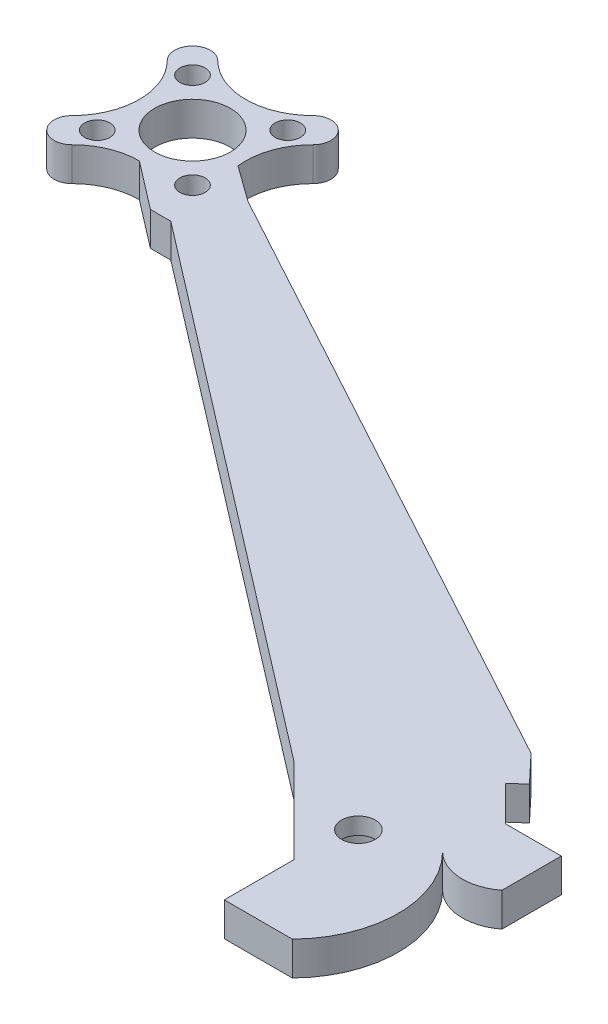
SolidWorks part; units mm, degrees
material "ABS"
ref_plane "Front Plane" through (0, 0, 0) normal (0, 0, 1) x (1, 0, 0)
ref_plane "Top Plane" through (0, 0, 0) normal (0, 1, 0) x (1, 0, 0)
ref_plane "Right Plane" through (0, 0, 0) normal (1, 0, 0) x (0, 0, -1)
sketch "Sketch1" plane through (0, 0, 0) normal (0, 1, 0) x (1, 0, 0)
  line L1 (8.155, -8.155) -> (-8.155, -8.155)
  line L2 (8.155, -8.155) -> (8.155, 8.155)
  line L3 (8.155, 8.155) -> (-8.155, 8.155)
  line L4 (-8.155, -8.155) -> (-8.155, 8.155)
  line L5 (8.155, -8.155) -> (-8.155, 8.155) construction
  line L6 (8.155, 8.155) -> (-8.155, -8.155) construction
  circle A0 centre (0, 0) radius 4.5
  dimension "D1" = 9
  dimension "D2" = 16.31
  dimension "D3" = 16.31
extrude "Boss-Extrude1" add sketch "Sketch1" along normal blind 4
sketch "Sketch3" plane through (0, 4, 0) normal (0, 1, 0) x (1, 0, 0)
  line L0 (0, 0) -> (0, 8.155) construction
  line L1 (8.155, 8.155) -> (-8.155, 8.155) construction
  line L2 (0, 0) -> (-8.155, 0) construction
  line L3 (-8.155, 8.155) -> (-8.155, -8.155) construction
  line L4 (0, 0) -> (0, -8.155) construction
  line L5 (-8.155, -8.155) -> (8.155, -8.155) construction
  line L6 (0, 0) -> (8.155, 0) construction
  line L7 (8.155, -8.155) -> (8.155, 8.155) construction
  line L8 (0, 0) -> (5.6569, 5.6569) construction
  line L9 (0, 0) -> (5.6569, -5.6569) construction
  line L10 (0, 0) -> (-5.6569, -5.6569) construction
  line L11 (0, 0) -> (-5.6569, 5.6569) construction
  circle A0 centre (5.6569, 5.6569) radius 1.5
  circle A1 centre (5.6569, -5.6569) radius 1.5
  circle A2 centre (-5.6569, -5.6569) radius 1.5
  circle A3 centre (-5.6569, 5.6569) radius 1.5
  point P22 (0, 0)
  point P29 (0, 0)
  dimension "D2" = 3
  dimension "D1" = 4
  dimension "D3" = 4
extrude "Cut-Extrude1" cut sketch "Sketch3" against normal blind 4
sketch "Sketch4" plane through (0, 4, 0) normal (0, 1, 0) x (1, 0, 0)
  line L0 (8.155, -8.155) -> (0, -8.155)
  line L1 (-8.155, -8.155) -> (8.155, -8.155) construction
  line L2 (8.155, -8.155) -> (8.155, 0)
  line L3 (8.155, -8.155) -> (8.155, 8.155) construction
  line L4 (0, -8.155) -> (0, -10.655)
  line L5 (8.155, 0) -> (10.655, 0)
  line L6 (0, -10.655) -> (10.655, -10.655)
  line L7 (10.655, -10.655) -> (10.655, 0)
extrude "Boss-Extrude2" add sketch "Sketch4" against normal blind 4
sketch "Sketch9" plane through (0, 4, 0) normal (0, 1, 0) x (1, 0, 0)
  line L0 (71.0614, -58.9826) -> (7.5931, -10.2817)
  line L1 (84.1935, -43.9826) -> (10.6138, -4.0321)
  line L2 (71.0614, -58.9826) -> (81.0614, -68.9826)
  line L3 (7.5931, -10.2817) -> (10.6138, -4.0321)
  line L4 (81.0614, -68.9826) -> (81.0614, -73.9826)
  line L5 (81.0614, -73.9826) -> (96.0614, -73.9826)
  line L6 (96.0614, -73.9826) -> (96.0614, -50.291)
  line L7 (96.0614, -50.291) -> (90.502, -50.291)
  line L8 (90.502, -50.291) -> (84.1935, -43.9826)
extrude "Boss-Extrude6" add sketch "Sketch9" against normal blind 4
sketch "Sketch12" plane through (0, 4, 0) normal (0, 1, 0) x (1, 0, 0)
  line L0 (87.2786, -47.2583) -> (85.7805, -48.5833)
  line L1 (85.7805, -48.5833) -> (89.9609, -52.761)
  line L2 (89.9609, -52.761) -> (90.502, -52.761)
  line L3 (90.502, -52.761) -> (96.0614, -52.761)
  line L4 (96.0614, -52.761) -> (96.0614, -50.291)
  line L5 (87.3477, -47.1368) -> (90.502, -50.291)
  line L6 (90.502, -50.291) -> (96.0614, -50.291)
  line L7 (90.502, -50.291) -> (96.0614, -50.291)
  line L8 (87.2786, -47.2583) -> (87.3477, -47.1368)
extrude "Cut-Extrude3" cut sketch "Sketch12" against normal blind 4 contours L8 L5 L6 L4 L3 L2 L1 L0
sketch "Sketch13" plane through (0, 4, 0) normal (0, 1, 0) x (1, 0, 0)
  line L0 (81.0614, -73.9826) -> (81.0614, -77.2826)
  line L1 (96.0614, -52.761) -> (96.5614, -52.761)
  line L2 (81.0614, -73.9826) -> (96.0614, -73.9826)
  line L3 (96.0614, -73.9826) -> (96.0614, -52.761)
  line L4 (96.5614, -52.761) -> (96.5614, -77.2826)
  line L5 (81.0614, -77.2826) -> (96.5614, -77.2826)
  dimension "D1" = 3.3
  dimension "D2" = 0.5
extrude "Boss-Extrude7" add sketch "Sketch13" against normal blind 4
sketch "Sketch16" plane through (0, 4, 0) normal (0, 1, 0) x (1, 0, 0)
  line L0 (0, -10.655) -> (-10, -10.655)
  line L1 (-10, -10.655) -> (-10, 10.345)
  line L2 (10.655, 0) -> (10.655, 10.345)
  line L3 (10.655, 10.345) -> (-10, 10.345)
  line L4 (0, -10.655) -> (0, -8.155)
  line L5 (0, -8.155) -> (-8.155, -8.155)
  line L6 (-8.155, -8.155) -> (-8.155, 8.155)
  line L7 (-8.155, 8.155) -> (8.155, 8.155)
  line L8 (8.155, 8.155) -> (8.155, 0)
  line L9 (8.155, 0) -> (10.655, 0)
  dimension "D1" = 10
  dimension "D2" = 21
extrude "Boss-Extrude9" add sketch "Sketch16" against normal blind 4
sketch "Sketch17" plane through (0, 4, 0) normal (0, 1, 0) x (1, 0, 0)
  line L0 (-5.6569, 5.6569) -> (-5.6569, 8.6569) construction
  line L1 (-5.6569, 5.6569) -> (-8.6569, 5.6569) construction
  line L2 (5.6569, 5.6569) -> (5.6569, 8.6569) construction
  line L3 (5.6569, 5.6569) -> (8.6569, 5.6569) construction
  line L4 (-5.6569, -5.6569) -> (-8.6569, -5.6569) construction
  line L5 (-5.6569, -5.6569) -> (-5.6569, -8.6569) construction
  line L6 (5.6569, -5.6569) -> (8.6569, -5.6569) construction
  line L7 (5.6569, -5.6569) -> (5.6569, -8.6569) construction
  line L8 (5.6569, -8.6569) -> (5.6569, -10.655)
  line L9 (-10, -10.655) -> (8.0797, -10.655) construction
  line L10 (8.6569, -5.6569) -> (10.655, -4.0544)
  line L11 (5.6569, -10.655) -> (8.0797, -10.655)
  line L12 (8.0797, -10.655) -> (71.0614, -58.9826)
  line L13 (71.0614, -58.9826) -> (81.0614, -68.9826)
  line L14 (81.0614, -68.9826) -> (81.0614, -77.2826)
  line L15 (81.0614, -77.2826) -> (96.5614, -77.2826)
  line L16 (96.5614, -77.2826) -> (96.5614, -52.761)
  line L17 (96.5614, -52.761) -> (89.9609, -52.761)
  line L18 (89.9609, -52.761) -> (85.7805, -48.5833)
  line L19 (85.7805, -48.5833) -> (87.2786, -47.2583)
  line L20 (87.2786, -47.2583) -> (84.1935, -43.9826)
  line L21 (84.1935, -43.9826) -> (10.655, -4.0544)
  arc A0 (-5.6569, -8.6569) -> (5.6569, -8.6569) centre (0, -14.3137) cw
  arc A1 (8.6569, 5.6569) -> (8.6569, -5.6569) centre (14.3137, 0) ccw
  arc A2 (5.6569, 8.6569) -> (-5.6569, 8.6569) centre (0, 14.3137) cw
  arc A3 (-8.6569, 5.6569) -> (-8.6569, -5.6569) centre (-14.3137, 0) cw
  arc A4 (-8.6569, 5.6569) -> (-5.6569, 8.6569) centre (-7.1569, 7.1569) cw
  arc A5 (5.6569, 8.6569) -> (8.6569, 5.6569) centre (7.1569, 7.1569) cw
  arc A6 (-8.6569, -5.6569) -> (-5.6569, -8.6569) centre (-7.1569, -7.1569) ccw
  dimension "D1" = 3
  dimension "D2" = 3
  dimension "D3" = 3
  dimension "D4" = 3
extrude "Cut-Extrude4" cut sketch "Sketch17" against normal blind 4 flip side to cut
sketch "Sketch18" plane through (0, 4, 0) normal (0, 1, 0) x (1, 0, 0)
  line L0 (5.6569, -10.655) -> (0, -6.3137)
  line L1 (0, -6.3137) -> (6.3728, -0.9706)
  line L2 (6.3728, -0.9706) -> (10.655, -4.0544)
  line L3 (10.655, -4.0544) -> (8.6569, -5.6569)
  line L4 (8.6569, -5.6569) -> (5.6569, -10.655)
  arc A0 (5.6569, -8.6569) -> (-5.6569, -8.6569) centre (0, -14.3137) ccw construction
  arc A1 (8.6569, 5.6569) -> (8.6569, -5.6569) centre (14.3137, 0) ccw construction
  circle A2 centre (5.6569, -5.6569) radius 1.5
extrude "Boss-Extrude10" add sketch "Sketch18" against normal blind 4
sketch "Sketch19" plane through (0, 4, 0) normal (0, 1, 0) x (1, 0, 0)
  line L0 (96.5614, -52.761) -> (97.0614, -52.761)
  line L1 (96.5614, -77.2826) -> (99.0224, -77.6438)
  line L2 (96.5614, -77.2826) -> (96.5614, -52.761)
  line L3 (97.0614, -52.761) -> (97.0614, -77.356)
  line L4 (97.0614, -77.356) -> (97.0614, -59.356)
  line L5 (97.0614, -77.356) -> (89.0614, -77.356)
  arc A0 (89.0614, -59.356) -> (89.0614, -77.356) centre (80.0614, -68.356) cw
  arc A1 (89.0614, -59.356) -> (97.0614, -59.356) centre (93.0614, -55.356) ccw
  dimension "D1" = 0.5
  dimension "D2" = 98.35
extrude "Cut-Extrude5" cut sketch "Sketch19" against normal blind 4 contours L4 A1 A0 L5
sketch "Sketch20" plane through (0, 0, 0) normal (0, -1, 0) x (1, 0, 0)
  line L0 (89.9609, 52.761) -> (81.8078, 62.1038) construction
  line L1 (89.9609, 52.761) -> (94.239, 52.761) construction
  line L2 (89.9609, 52.761) -> (96.5614, 52.761) construction
  circle A0 centre (81.8078, 62.1038) radius 2
  dimension "D3" = 4
  dimension "D1" = 12.4
  dimension "D2" = 131.11
extrude "Cut-Extrude6" cut sketch "Sketch20" against normal blind 10
sketch "Sketch21" plane through (0, 0, 0) normal (0, -1, 0) x (1, 0, 0)
  circle A0 centre (81.8078, 62.1038) radius 3
  dimension "D1" = 6
extrude "Cut-Extrude7" cut sketch "Sketch21" against normal blind 2
